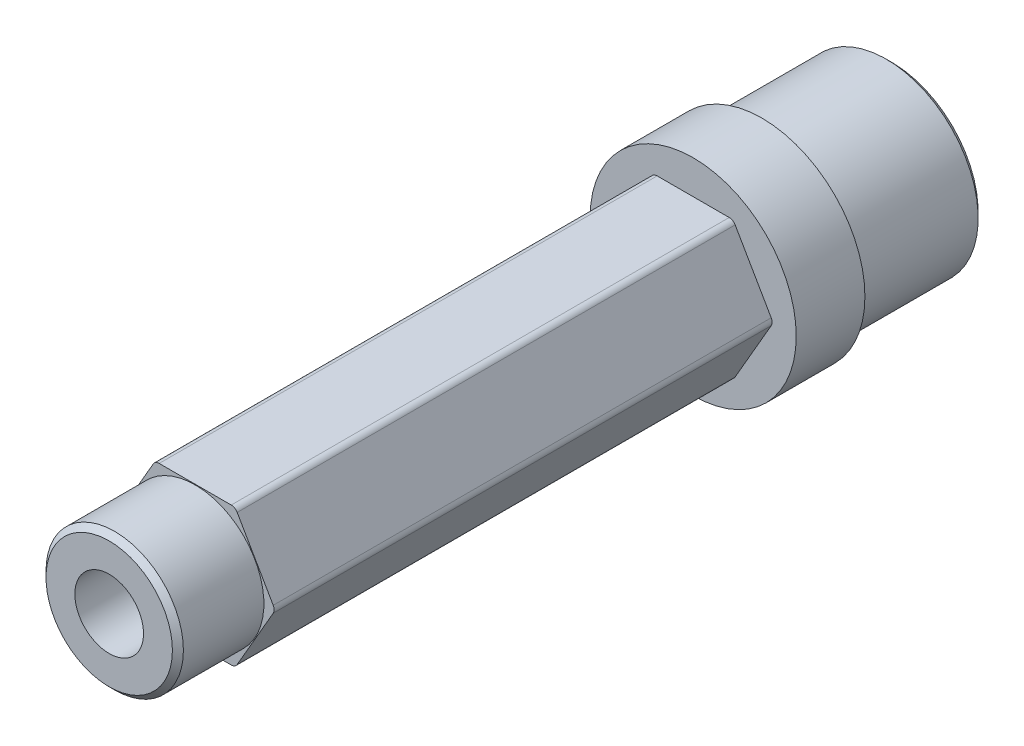
SolidWorks part; units mm, degrees
material "6061-T6 (SS)"
ref_plane "Front Plane" through (0, 0, 0) normal (0, 0, 1) x (1, 0, 0)
ref_plane "Top Plane" through (0, 0, 0) normal (0, 1, 0) x (1, 0, 0)
ref_plane "Right Plane" through (0, 0, 0) normal (1, 0, 0) x (0, 0, -1)
sketch "Sketch2" plane through (0, 0, 0) normal (1, 0, 0) x (0, 0, -1)
  line L0 (0, 0) -> (-59728.3895, 0) construction
  line L1 (0, 3.175) -> (0, 6.35)
  line L2 (0, 6.35) -> (7.9502, 6.35)
  line L3 (7.9502, 6.35) -> (7.9502, 7.62)
  line L4 (7.9502, 7.62) -> (53.9827, 7.62)
  line L7 (53.9827, 7.62) -> (53.9827, 9.525)
  line L8 (53.9827, 9.525) -> (60.3327, 9.525)
  line L9 (60.3327, 9.525) -> (60.3327, 8.5)
  line L10 (60.3327, 8.5) -> (72.3327, 8.5)
  line L11 (72.3327, 8.5) -> (72.3327, 0)
  line L12 (72.3327, 0) -> (6.858, 0)
  line L13 (0, 3.175) -> (6.858, 3.175)
  line L14 (6.858, 3.175) -> (6.858, 0)
  dimension "D2" = 7.9502
  dimension "D3" = 12.7
  dimension "D4" = 15.24
  dimension "D5" = 46.0325
  dimension "D6" = 6.35
  dimension "D7" = 6.35
  dimension "D8" = 17
  dimension "D9" = 19.05
  dimension "D10" = 12
  dimension "D11" = 6.858
revolve "Revolve1" add sketch "Sketch2" angle 360 about L0
sketch "Sketch3" plane through (0, 0, -7.9502) normal (0, 0, 1) x (1, 0, 0)
  line L1 (3.697, 6.4033) -> (-3.697, 6.4033)
  line L2 (-3.697, 6.4033) -> (-7.3939, 0)
  line L3 (-7.3939, 0) -> (-3.697, -6.4033)
  line L4 (-3.697, -6.4033) -> (3.697, -6.4033)
  line L5 (3.697, -6.4033) -> (7.3939, 0)
  line L6 (7.3939, 0) -> (3.697, 6.4033)
  circle A0 centre (0, 0) radius 6.4033 construction
  dimension "D1" = 12.8067
extrude "Cut-Extrude1" cut sketch "Sketch3" against normal up to surface (46.0325 mm away) flip side to cut up to face at (-7.62, 0, -53.9827)
chamfer "Chamfer1" distance 0.508 angle 45 2 edges at (-8.5, 0, -72.3327) (-6.35, 0, 0)
fillet "Fillet1" radius 0.635 6 edges at (3.697, -6.4033, -30.9665) (-3.697, -6.4033, -30.9665) (-7.3939, 0, -30.9665) (-3.697, 6.4033, -30.9665) (3.697, 6.4033, -30.9665) (7.3939, 0, -30.9665)
